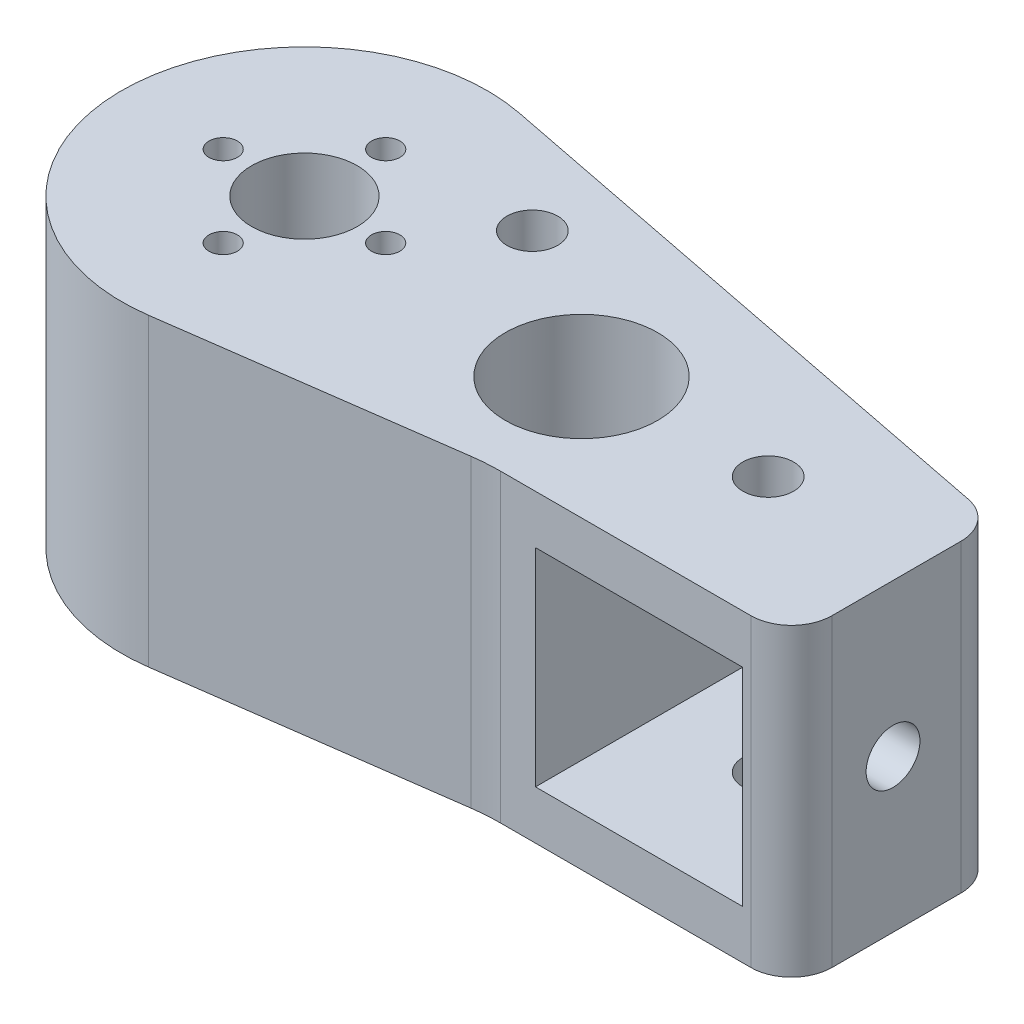
SolidWorks part; units mm, degrees
ref_plane "Front Plane" through (0, 0, 0) normal (0, 0, 1) x (1, 0, 0)
ref_plane "Top Plane" through (0, 0, 0) normal (0, 1, 0) x (1, 0, 0)
ref_plane "Right Plane" through (0, 0, 0) normal (1, 0, 0) x (0, 0, -1)
sketch "Sketch1" plane through (0, 0, 0) normal (0, 1, 0) x (1, 0, 0)
  line L1 (-15, 10) -> (15, 10)
  line L2 (-15, 10) -> (-15, -10)
  line L3 (-15, -10) -> (15, -10)
  line L4 (15, 10) -> (15, -10)
  line L5 (-15, 10) -> (15, -10) construction
  line L6 (-15, -10) -> (15, 10) construction
  point P0 (0, 0)
  dimension "D1" = 30
  dimension "D2" = 20
extrude "Boss-Extrude1" add sketch "Sketch1" along normal blind 30
sketch "Sketch3" plane through (0, 30, 0) normal (0, 1, 0) x (1, 0, 0)
  line L0 (15, 10) -> (-15, 10) construction
  line L1 (-17.7223, 9.5532) -> (-17.7223, -5.4468)
  line L3 (-17.7223, -5.4468) -> (-17.7223, -10.3753) construction
  line L4 (-15, -10) -> (-44.2809, -14.0365)
  line L5 (-43.2662, 21.4567) -> (15, 10)
  line L8 (-17.7223, 9.5532) -> (-17.7223, 16.4341)
  line L9 (-15, -10) -> (-15, 10)
  line L10 (-15, 10) -> (15, 10)
  circle A0 centre (-17.7223, 2.0532) radius 7.5
  circle A1 centre (-46.739, 3.7949) radius 5.2
  circle A3 centre (-46.739, 3.7949) radius 8 construction
  circle A4 centre (-46.739, -4.2051) radius 1.4
  circle A5 centre (-54.739, 3.7949) radius 1.4
  circle A6 centre (-46.739, 3.7949) radius 5.2
  circle A7 centre (-46.739, 11.7949) radius 1.4
  circle A8 centre (-46.739, 3.7949) radius 5.2
  circle A9 centre (-38.739, 3.7949) radius 1.4
  circle A10 centre (-46.739, 3.7949) radius 5.2
  arc A12 (-43.2662, 21.4567) -> (-44.2809, -14.0365) centre (-46.739, 3.7949) ccw
  point P7 (0, 0)
  point P8 (0, 0)
  point P12 (-17.7223, 2.0532)
  point P22 (-46.739, 3.7949)
  point P23 (0, 0)
  point P25 (0, 0)
  point P29 (0, 0)
  point P32 (0, 0)
  line M6 (15, 10) -> (-15, 10)
  line M7 (-15, 10) -> (-15, -10)
  dimension "D1" = 15
  dimension "D2" = 10.4
  dimension "D3" = 16
  dimension "D4" = 2.8
  dimension "D6" = 18
  dimension "D5" = 4
extrude "Boss-Extrude2" add sketch "Sketch3" against normal blind 30 contours A0 L5 L8 M7 M6 | L5 A12 L4 A0 L8 A1 A4 A5 A7 A9 M7
sketch "Sketch2" plane through (0, 0, 10) normal (0, 0, 1) x (1, 0, 0)
  line L1 (-10.2, 4.8) -> (10.2, 4.8)
  line L2 (-10.2, 4.8) -> (-10.2, 25.2)
  line L3 (-10.2, 25.2) -> (10.2, 25.2)
  line L4 (10.2, 4.8) -> (10.2, 25.2)
  line L5 (-10.2, 4.8) -> (10.2, 25.2) construction
  line L6 (-10.2, 25.2) -> (10.2, 4.8) construction
  line L10 (15, 30) -> (-15, 0) construction
  point P0 (0, 15)
  point P6 (0, 15)
  dimension "D4" = 20.4
extrude "Cut-Extrude1" cut sketch "Sketch2" against normal through all
sketch "Sketch9" plane through (0, 30, 0) normal (0, 1, 0) x (1, 0, 0)
  circle A0 centre (-17.7223, 2.0532) radius 7.5
extrude "Cut-Extrude5" cut sketch "Sketch9" against normal through all
sketch "Sketch5" plane through (0, 0, 0) normal (0, -1, 0) x (1, 0, 0)
  circle A0 centre (-17.7223, -2.0532) radius 8.0543
  circle A1 centre (-17.7223, -2.0532) radius 5.25
  dimension "D1" = 10.5
extrude "Boss-Extrude3" add sketch "Sketch5" against normal blind 4
sketch "Sketch7" plane through (0, 30, 0) normal (0, 1, 0) x (1, 0, 0)
  line L0 (0, 23.4136) -> (0, -10) construction
  line L2 (-15, -10) -> (15, -10) construction
  line L3 (0, 2.7111) -> (-32.5711, 12.0624)
  circle A0 centre (0, 2.7111) radius 2.5
  circle A3 centre (-46.739, 3.7949) radius 11 construction
  circle A4 centre (-32.5711, 12.0624) radius 4 construction
  circle A5 centre (-32.5711, 12.0624) radius 2.5
  point P8 (-16.9157, -3.0499)
  dimension "D1" = 5
  dimension "D2" = 22
  dimension "D3" = 8
extrude "Cut-Extrude3" cut sketch "Sketch7" against normal through all
sketch "Sketch8" plane through (0, 30, 0) normal (0, 1, 0) x (1, 0, 0)
  line L1 (-33.6636, 19.9874) -> (-39.9807, 15.0788)
  line L2 (-39.9807, 15.0788) -> (-38.8882, 7.1537)
  line L3 (-38.8882, 7.1537) -> (-31.4786, 4.1373)
  line L4 (-31.4786, 4.1373) -> (-25.1616, 9.046)
  line L5 (-25.1616, 9.046) -> (-26.2541, 16.9711)
  line L6 (-26.2541, 16.9711) -> (-33.6636, 19.9874)
  line L7 (-38.8882, 7.1537) -> (-41.0614, 22.9182)
  line L8 (-41.0614, 22.9182) -> (-27.3348, 24.8105)
  line L9 (-27.3348, 24.8105) -> (-25.1616, 9.046)
  line L11 (-15, -10) -> (-44.2809, -14.0365) construction
  circle A0 centre (-32.5711, 12.0624) radius 6.9282 construction
  circle M7 centre (-32.5711, 12.0624) radius 2.5
  line M11 (15, 10) -> (-43.2662, 21.4567)
  dimension "D1" = 8
extrude "Cut-Extrude4" cut sketch "Sketch8" against normal blind 6 from offset 10 contours L5 L6 L1 L2 L3 L4 M11 M7 | L9 L8 L7 L1 L6 M11 | L9 L6 M11 | L7 L1 M11 | L6 L1 M11 offset against normal yes
fillet "Fillet1" radius 20 1 edges at (-15, 15, 10)
sketch "Sketch10" plane through (15, 0, 0) normal (1, 0, 0) x (0, 0, -1)
  line L0 (-10, 30) -> (10, 0) construction
  circle A0 centre (0, 15) radius 2.65
  dimension "D1" = 5.3
extrude "Cut-Extrude6" cut sketch "Sketch10" against normal blind 16
fillet "Fillet2" radius 4 2 edges at (15, 15, -10) (15, 15, 10)
